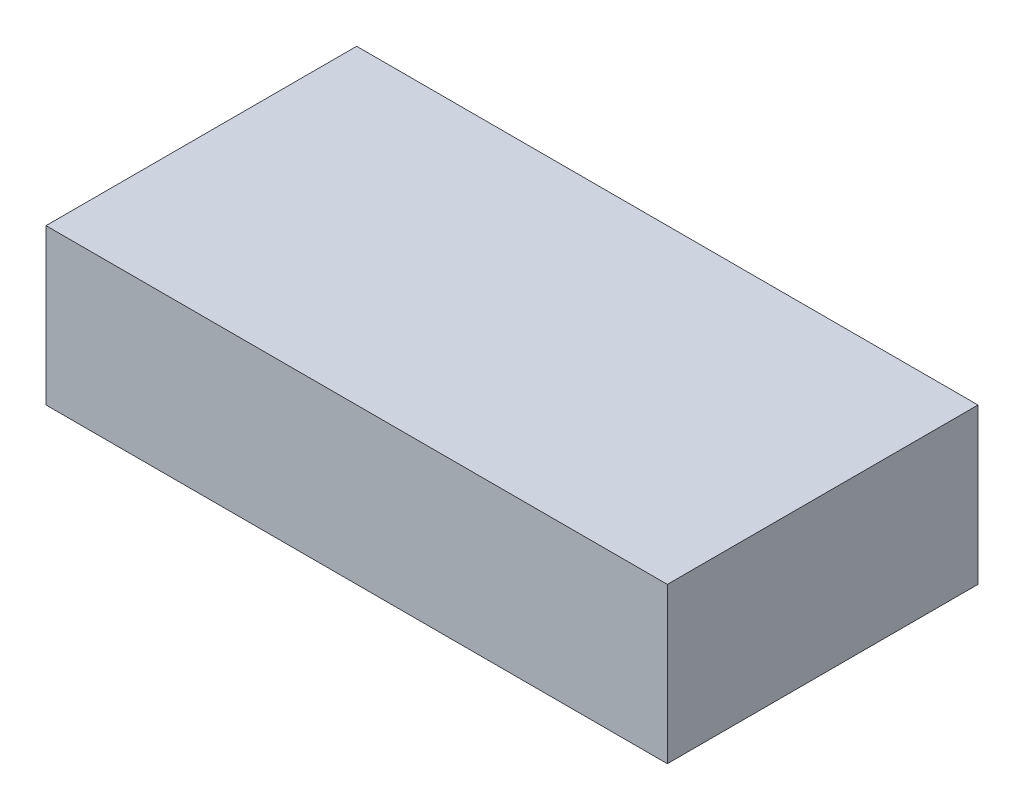
SolidWorks part; units mm, degrees
ref_plane "Front Plane" through (0, 0, 0) normal (0, 0, 1) x (1, 0, 0)
ref_plane "Top Plane" through (0, 0, 0) normal (0, 1, 0) x (1, 0, 0)
ref_plane "Right Plane" through (0, 0, 0) normal (1, 0, 0) x (0, 0, -1)
sketch "Sketch1" plane through (0, 0, 0) normal (0, 1, 0) x (1, 0, 0)
  line L1 (0, 0) -> (101.6, 0)
  line L2 (0, 0) -> (0, 50.8)
  line L3 (0, 50.8) -> (101.6, 50.8)
  line L4 (101.6, 0) -> (101.6, 50.8)
  dimension "D1" = 50.8
  dimension "D2" = 101.6
extrude "Boss-Extrude1" add sketch "Sketch1" along normal blind 25.4
